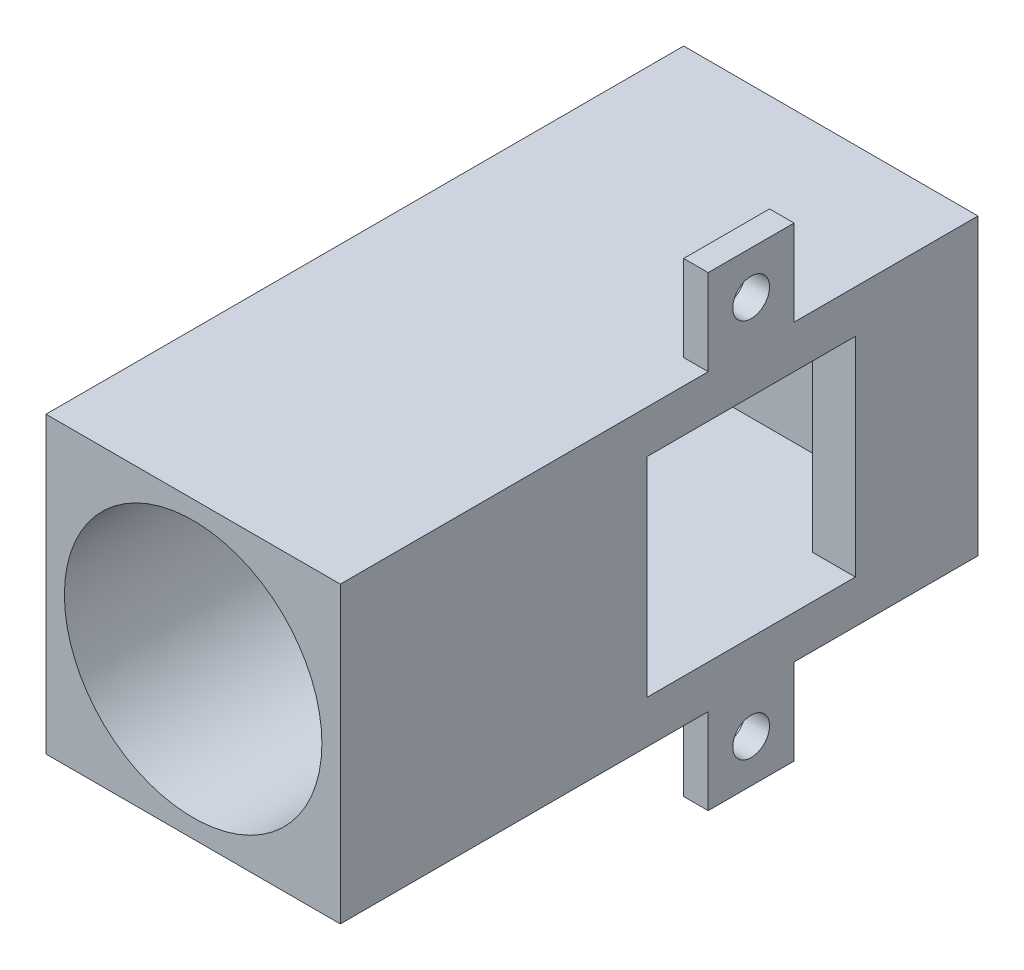
SolidWorks part; units mm, degrees
ref_plane "Спереди" through (0, 0, 0) normal (0, 0, 1) x (1, 0, 0)
ref_plane "Сверху" through (0, 0, 0) normal (0, 1, 0) x (1, 0, 0)
ref_plane "Справа" through (0, 0, 0) normal (1, 0, 0) x (0, 0, -1)
sketch "Эскиз1" plane through (0, 0, 0) normal (0, 0, 1) x (1, 0, 0)
  line L1 (12, 12) -> (-12, 12)
  line L2 (-12, 12) -> (-12, -12)
  line L3 (-12, -12) -> (12, -12)
  line L4 (12, -12) -> (12, 12)
  dimension "D1" = 24
  dimension "D2" = 24
  dimension "D3" = 12
  dimension "D4" = 12
extrude "Бобышка-Вытянуть1" add sketch "Эскиз1" along normal blind 42 and the other way blind 10
sketch "Эскиз3" plane through (0, 0, 42) normal (0, 0, 1) x (1, 0, 0)
  circle A0 centre (0, 0) radius 10.5
extrude "Вырез-Вытянуть1" cut sketch "Эскиз3" against normal blind 20
sketch "Эскиз4" plane through (0, 0, 22) normal (0, 0, 1) x (1, 0, 0)
  line L1 (8.5, 8.5) -> (-8.5, 8.5)
  line L2 (8.5, 8.5) -> (8.5, -8.5)
  line L3 (8.5, -8.5) -> (-8.5, -8.5)
  line L4 (-8.5, 8.5) -> (-8.5, -8.5)
  line L5 (8.5, 8.5) -> (-8.5, -8.5) construction
  line L6 (8.5, -8.5) -> (-8.5, 8.5) construction
  point P0 (0, 0)
extrude "Вырез-Вытянуть2" cut sketch "Эскиз4" against normal blind 29
sketch "Эскиз5" plane through (12, 0, 0) normal (1, 0, 0) x (0, 0, -1)
  line L0 (-42, 12) -> (10, 12) construction
  line L1 (0, -8.5) -> (-17, -8.5)
  line L7 (0, 8.5) -> (0, -8.5)
  line L8 (-17, -8.5) -> (-17, 8.5)
  line L9 (-17, 8.5) -> (0, 8.5)
  line L11 (10, -12) -> (10, 12) construction
  dimension "D1" = 17
  dimension "D2" = 17
  dimension "D3" = 3.5
  dimension "D4" = 10
extrude "Вырез-Вытянуть5" cut sketch "Эскиз5" against normal through all
sketch "Эскиз6" plane through (12, 0, 0) normal (1, 0, 0) x (0, 0, -1)
  line L1 (-8.5, 8.5) -> (-8.5, -8.5) construction
  line L2 (-42, 12) -> (10, 12) construction
  line L3 (-5, 12) -> (-12, 12)
  line L5 (-5, 12) -> (-5, 19)
  line L6 (-5, 19) -> (-12, 19)
  line L7 (-12, 19) -> (-12, 12)
  line L11 (0, 8.5) -> (-17, 8.5) construction
  line L12 (-42, -12) -> (10, -12) construction
  line L14 (-12, -12) -> (-12, -19)
  line L15 (-12, -19) -> (-5, -19)
  line L16 (-5, -19) -> (-5, -12)
  line L17 (-5, -12) -> (-12, -12)
  line L18 (-17, -8.5) -> (0, -8.5) construction
  line L19 (-17, 0) -> (0, 0) construction
  line L20 (-17, 8.5) -> (-17, -8.5) construction
  circle A0 centre (-8.5, -15.5) radius 1.5
  circle A1 centre (-8.5, 15.5) radius 1.5
  dimension "D1" = 3.5
  dimension "D3" = 3
  dimension "D4" = 3
  dimension "D2" = 3.5
  dimension "D5" = 7
  dimension "D6" = 7
  dimension "D7" = 0
  dimension "D8" = 7
  dimension "D9" = 3.5
  dimension "D10" = 3.5
  dimension "D11" = 0
  dimension "D12" = 7
extrude "Бобышка-Вытянуть2" add sketch "Эскиз6" against normal blind 2
sketch "Эскиз8" plane through (0, 0, -10) normal (0, 0, -1) x (-1, 0, 0)
